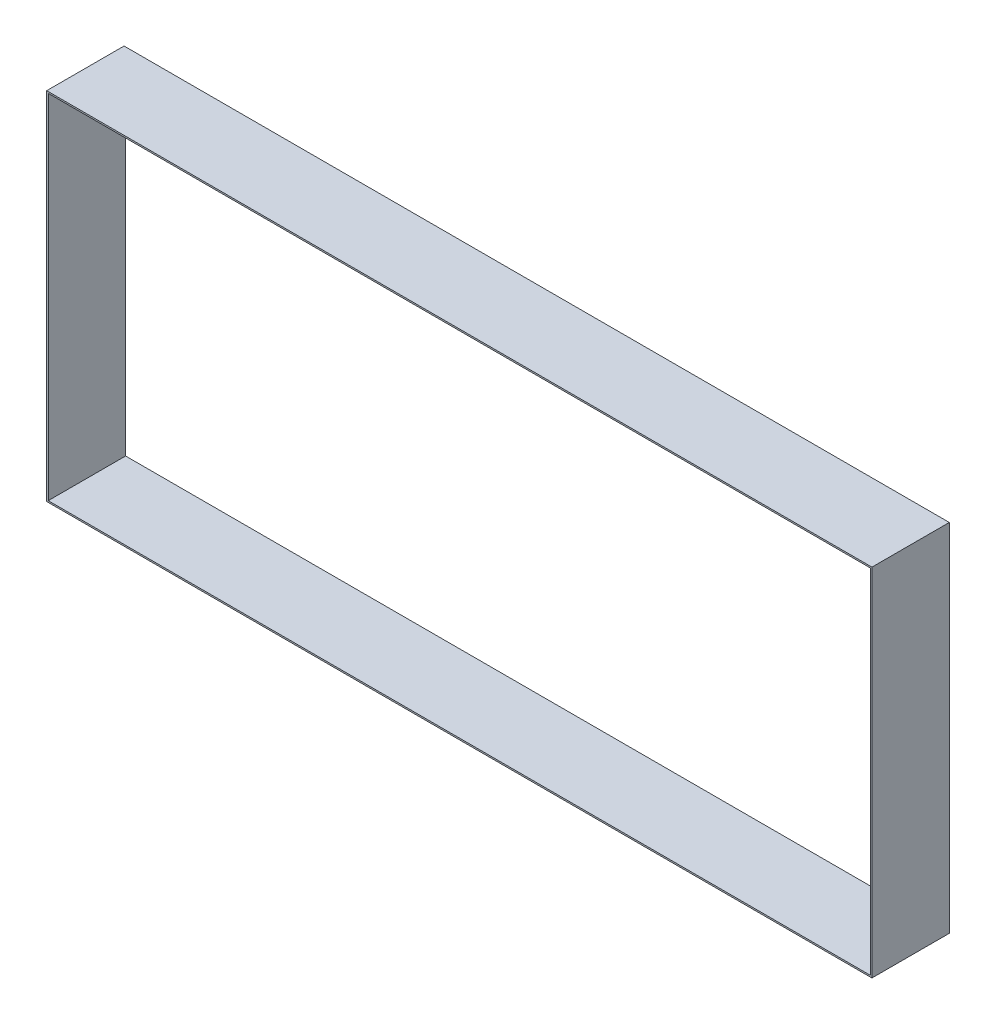
SolidWorks part; units mm, degrees
ref_plane "Front Plane" through (0, 0, 0) normal (0, 0, 1) x (1, 0, 0)
ref_plane "Top Plane" through (0, 0, 0) normal (0, 1, 0) x (1, 0, 0)
ref_plane "Right Plane" through (0, 0, 0) normal (1, 0, 0) x (0, 0, -1)
sketch "Sketch1" plane through (0, 0, 0) normal (0, 0, 1) x (1, 0, 0)
  line L1 (-57.8684, 31.1412) -> (475.5316, 31.1412)
  line L2 (-57.8684, 31.1412) -> (-57.8684, -198.8588)
  line L3 (-57.8684, -198.8588) -> (475.5316, -198.8588)
  line L4 (475.5316, 31.1412) -> (475.5316, -198.8588)
  line L5 (-56.8684, 30.1412) -> (474.5316, 30.1412)
  line L6 (-56.8684, 30.1412) -> (-56.8684, -197.8588)
  line L7 (-56.8684, -197.8588) -> (474.5316, -197.8588)
  line L8 (474.5316, 30.1412) -> (474.5316, -197.8588)
  dimension "D1" = 533.4
  dimension "D2" = 230
  dimension "D3" = 1
  dimension "D4" = 1
  dimension "D5" = 1
  dimension "D6" = 1
extrude "Boss-Extrude1" add sketch "Sketch1" along normal blind 50
